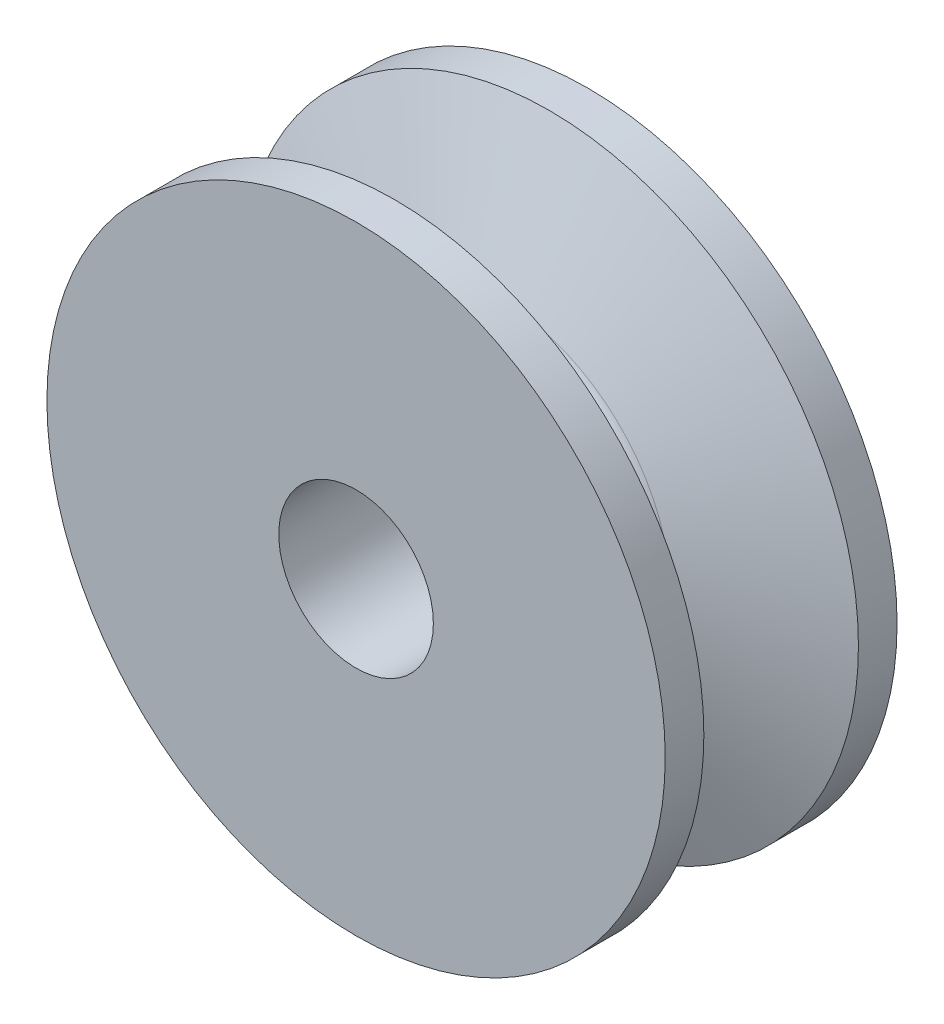
SolidWorks part; units mm, degrees
ref_plane "Plan de face" through (0, 0, 0) normal (0, 0, 1) x (1, 0, 0)
ref_plane "Plan de dessus" through (0, 0, 0) normal (0, 1, 0) x (1, 0, 0)
ref_plane "Plan de droite" through (0, 0, 0) normal (1, 0, 0) x (0, 0, -1)
sketch "Esquisse1" plane through (0, 0, 0) normal (0, 0, 1) x (1, 0, 0)
  circle A0 centre (0, 0) radius 20
  dimension "D1" = 40
extrude "Boss.-Extru.1" add sketch "Esquisse1" along normal mid plane 15
sketch "Esquisse4" plane through (0, 0, 0) normal (1, 0, 0) x (0, 0, -1)
  line L0 (-5, 20) -> (-1.3249, 10)
  line L1 (7.5, 20) -> (-7.5, 20) construction
  line L2 (-1.3249, 10) -> (1.3249, 10)
  line L3 (1.3249, 10) -> (5, 20)
  line L4 (5, 20) -> (-5, 20)
  line L5 (-15.7886, 0) -> (16.0217, 0) construction
  point P4 (0, 20)
  point P7 (0, 10)
  dimension "D1" = 10
  dimension "D2" = 10
  dimension "D3" = 3.6751
revolve "Enlèvement de matière-Révolution1" cut sketch "Esquisse4" angle 360 about L5
fillet "Congé1" radius 1.7 1 edges at (10, 0, -1.3249)
fillet "Congé3" radius 1.7 1 edges at (10, 0, 1.3249)
sketch "Esquisse5" plane through (0, 0, 7.5) normal (0, 0, 1) x (1, 0, 0)
  circle A0 centre (0, 0) radius 5
  dimension "D1" = 10
extrude "Enlèv. mat.-Extru.1" cut sketch "Esquisse5" against normal through all
